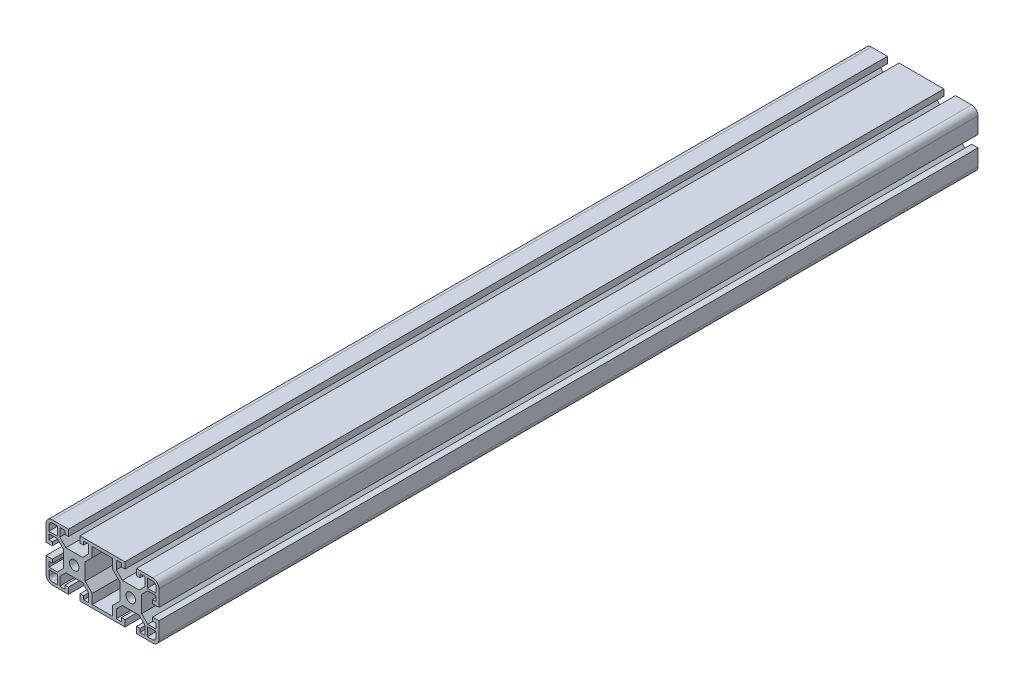
SolidWorks part; units mm, degrees
ref_plane "Front Plane" through (0, 0, 0) normal (0, 0, 1) x (1, 0, 0)
ref_plane "Top Plane" through (0, 0, 0) normal (0, 1, 0) x (1, 0, 0)
ref_plane "Right Plane" through (0, 0, 0) normal (1, 0, 0) x (0, 0, -1)
sketch "Sketch1" plane through (0, 0, 0) normal (0, 0, 1) x (1, 0, 0)
  line L0 (0, 17.8) -> (0, -17.8) construction
  line B0 (38, -15.5) -> (38, -11.75)
  line B1 (38, -11.75) -> (31.75, -11.75)
  line B2 (31.75, -11.75) -> (31.75, -18)
  line B3 (31.75, -18) -> (35.5, -18)
  arc B4 (35.5, -18) -> (38, -15.5) centre (35.5, -15.5) ccw
  line B5 (-38, 15.5) -> (-38, 11.75)
  line B6 (-38, 11.75) -> (-31.75, 11.75)
  line B7 (-31.75, 11.75) -> (-31.75, 18)
  line B8 (-31.75, 18) -> (-35.5, 18)
  arc B9 (-35.5, 18) -> (-38, 15.5) centre (-35.5, 15.5) ccw
  line B10 (24.1, -20) -> (35.5, -20)
  arc B11 (35.5, -20) -> (40, -15.5) centre (35.5, -15.5) ccw
  line B12 (40, -15.5) -> (40, -4.1)
  line B13 (40, -4.1) -> (35.5, -4.1)
  line B14 (35.5, -4.1) -> (35.5, -6.6)
  line B15 (35.5, -6.6) -> (38, -6.6)
  line B16 (38, -6.6) -> (38, -10.25)
  line B17 (38, -10.25) -> (32.0178, -10.25)
  line B18 (32.0178, -10.25) -> (27.7, -5.9322)
  line B19 (27.7, -5.9322) -> (27.7, 5.9322)
  line B20 (27.7, 5.9322) -> (32.0178, 10.25)
  line B21 (32.0178, 10.25) -> (38, 10.25)
  line B22 (38, 10.25) -> (38, 6.6)
  line B23 (38, 6.6) -> (35.5, 6.6)
  line B24 (35.5, 6.6) -> (35.5, 4.1)
  line B25 (35.5, 4.1) -> (40, 4.1)
  line B26 (40, 4.1) -> (40, 15.5)
  arc B27 (40, 15.5) -> (35.5, 20) centre (35.5, 15.5) ccw
  line B28 (35.5, 20) -> (24.1, 20)
  line B29 (24.1, 20) -> (24.1, 15.5)
  line B30 (24.1, 15.5) -> (26.6, 15.5)
  line B31 (26.6, 15.5) -> (26.6, 18)
  line B32 (26.6, 18) -> (30.25, 18)
  line B33 (30.25, 18) -> (30.25, 12.0178)
  line B34 (30.25, 12.0178) -> (25.9322, 7.7)
  line B35 (25.9322, 7.7) -> (14.0678, 7.7)
  line B36 (14.0678, 7.7) -> (9.75, 12.0178)
  line B37 (9.75, 12.0178) -> (9.75, 18)
  line B38 (9.75, 18) -> (13.4, 18)
  line B39 (13.4, 18) -> (13.4, 15.5)
  line B40 (13.4, 15.5) -> (15.9, 15.5)
  line B41 (15.9, 15.5) -> (15.9, 20)
  line B42 (15.9, 20) -> (-15.9, 20)
  line B43 (-15.9, 20) -> (-15.9, 15.5)
  line B44 (-15.9, 15.5) -> (-13.4, 15.5)
  line B45 (-13.4, 15.5) -> (-13.4, 18)
  line B46 (-13.4, 18) -> (-9.75, 18)
  line B47 (-9.75, 18) -> (-9.75, 12.0178)
  line B48 (-9.75, 12.0178) -> (-14.0678, 7.7)
  line B49 (-14.0678, 7.7) -> (-25.9322, 7.7)
  line B50 (-25.9322, 7.7) -> (-30.25, 12.0178)
  line B51 (-30.25, 12.0178) -> (-30.25, 18)
  line B52 (-30.25, 18) -> (-26.6, 18)
  line B53 (-26.6, 18) -> (-26.6, 15.5)
  line B54 (-26.6, 15.5) -> (-24.1, 15.5)
  line B55 (-24.1, 15.5) -> (-24.1, 20)
  line B56 (-24.1, 20) -> (-35.5, 20)
  arc B57 (-35.5, 20) -> (-40, 15.5) centre (-35.5, 15.5) ccw
  line B58 (-40, 15.5) -> (-40, 4.1)
  line B59 (-40, 4.1) -> (-35.5, 4.1)
  line B60 (-35.5, 4.1) -> (-35.5, 6.6)
  line B61 (-35.5, 6.6) -> (-38, 6.6)
  line B62 (-38, 6.6) -> (-38, 10.25)
  line B63 (-38, 10.25) -> (-32.0178, 10.25)
  line B64 (-32.0178, 10.25) -> (-27.7, 5.9322)
  line B65 (-27.7, 5.9322) -> (-27.7, -5.9322)
  line B66 (-27.7, -5.9322) -> (-32.0178, -10.25)
  line B67 (-32.0178, -10.25) -> (-38, -10.25)
  line B68 (-38, -10.25) -> (-38, -6.6)
  line B69 (-38, -6.6) -> (-35.5, -6.6)
  line B70 (-35.5, -6.6) -> (-35.5, -4.1)
  line B71 (-35.5, -4.1) -> (-40, -4.1)
  line B72 (-40, -4.1) -> (-40, -15.5)
  arc B73 (-40, -15.5) -> (-35.5, -20) centre (-35.5, -15.5) ccw
  line B74 (-35.5, -20) -> (-24.1, -20)
  line B75 (-24.1, -20) -> (-24.1, -15.5)
  line B76 (-24.1, -15.5) -> (-26.6, -15.5)
  line B77 (-26.6, -15.5) -> (-26.6, -18)
  line B78 (-26.6, -18) -> (-30.25, -18)
  line B79 (-30.25, -18) -> (-30.25, -12.0178)
  line B80 (-30.25, -12.0178) -> (-25.9322, -7.7)
  line B81 (-25.9322, -7.7) -> (-14.0678, -7.7)
  line B82 (-14.0678, -7.7) -> (-9.75, -12.0178)
  line B83 (-9.75, -12.0178) -> (-9.75, -18)
  line B84 (-9.75, -18) -> (-13.4, -18)
  line B85 (-13.4, -18) -> (-13.4, -15.5)
  line B86 (-13.4, -15.5) -> (-15.9, -15.5)
  line B87 (-15.9, -15.5) -> (-15.9, -20)
  line B88 (-15.9, -20) -> (15.9, -20)
  line B89 (15.9, -20) -> (15.9, -15.5)
  line B90 (15.9, -15.5) -> (13.4, -15.5)
  line B91 (13.4, -15.5) -> (13.4, -18)
  line B92 (13.4, -18) -> (9.75, -18)
  line B93 (9.75, -18) -> (9.75, -12.0178)
  line B94 (9.75, -12.0178) -> (14.0678, -7.7)
  line B95 (14.0678, -7.7) -> (25.9322, -7.7)
  line B96 (25.9322, -7.7) -> (30.25, -12.0178)
  line B97 (30.25, -12.0178) -> (30.25, -18)
  line B98 (30.25, -18) -> (26.6, -18)
  line B99 (26.6, -18) -> (26.6, -15.5)
  line B100 (26.6, -15.5) -> (24.1, -15.5)
  line B101 (24.1, -15.5) -> (24.1, -20)
  line B102 (-7.25, -10.9822) -> (-7.25, -17.8)
  line B103 (-7.25, -17.8) -> (7.25, -17.8)
  line B104 (7.25, -17.8) -> (7.25, -10.9822)
  line B105 (7.25, -10.9822) -> (12.3, -5.9322)
  line B106 (12.3, -5.9322) -> (12.3, 5.9322)
  line B107 (12.3, 5.9322) -> (7.25, 10.9822)
  line B108 (7.25, 10.9822) -> (7.25, 17.8)
  line B109 (7.25, 17.8) -> (-7.25, 17.8)
  line B110 (-7.25, 17.8) -> (-7.25, 10.9822)
  line B111 (-7.25, 10.9822) -> (-12.3, 5.9322)
  line B112 (-12.3, 5.9322) -> (-12.3, -5.9322)
  line B113 (-12.3, -5.9322) -> (-7.25, -10.9822)
  circle B114 centre (-20, 0) radius 3.4
  circle B115 centre (20, 0) radius 3.4
  line B116 (-35.5, -18) -> (-31.75, -18)
  line B117 (-31.75, -18) -> (-31.75, -11.75)
  line B118 (-31.75, -11.75) -> (-38, -11.75)
  line B119 (-38, -11.75) -> (-38, -15.5)
  arc B120 (-38, -15.5) -> (-35.5, -18) centre (-35.5, -15.5) ccw
  line B121 (35.5, 18) -> (31.75, 18)
  line B122 (31.75, 18) -> (31.75, 11.75)
  line B123 (31.75, 11.75) -> (38, 11.75)
  line B124 (38, 11.75) -> (38, 15.5)
  arc B125 (38, 15.5) -> (35.5, 18) centre (35.5, 15.5) ccw
sketch_block_instance "S8-4080-1"
sketch_block "S8-4080"
extrude "Boss-Extrude1" add sketch "Sketch1" along normal blind 580
